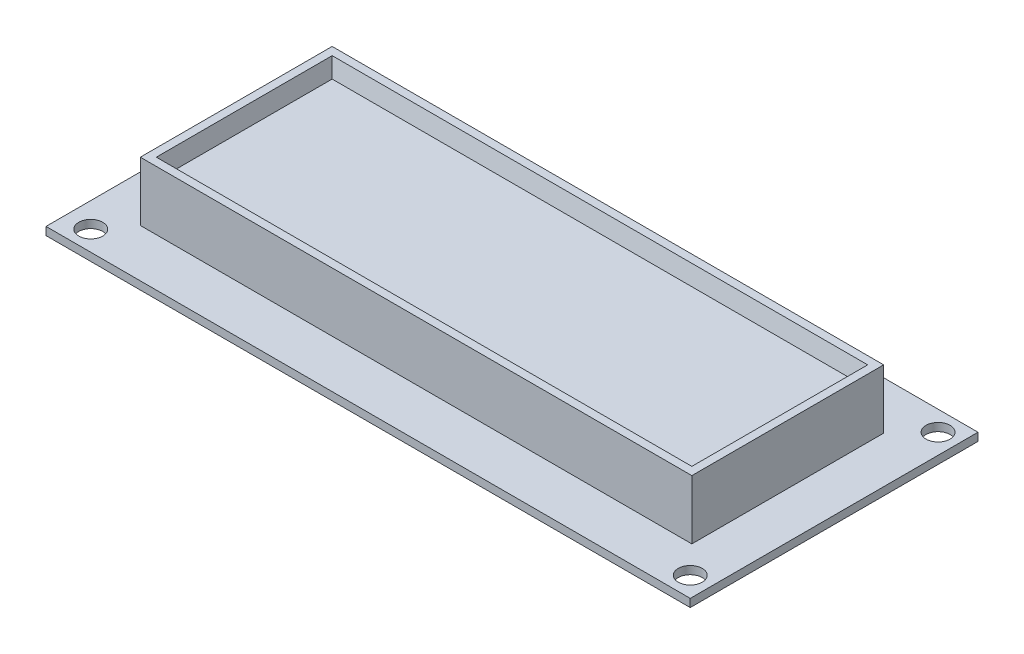
SolidWorks part; units mm, degrees
ref_plane "Front Plane" through (0, 0, 0) normal (0, 0, 1) x (1, 0, 0)
ref_plane "Top Plane" through (0, 0, 0) normal (0, 1, 0) x (1, 0, 0)
ref_plane "Right Plane" through (0, 0, 0) normal (1, 0, 0) x (0, 0, -1)
sketch "Sketch1" plane through (0, 0, 0) normal (0, 1, 0) x (1, 0, 0)
  line L1 (0, 0) -> (80.6, 0)
  line L2 (0, 0) -> (0, 36)
  line L3 (0, 36) -> (80.6, 36)
  line L4 (80.6, 0) -> (80.6, 36)
  dimension "D1" = 36
  dimension "D2" = 80.6
extrude "Boss-Extrude1" add sketch "Sketch1" along normal blind 1
sketch "Sketch2" plane through (0, 1, 0) normal (0, 1, 0) x (1, 0, 0)
  line L0 (80.6, 36) -> (0, 36) construction
  line L1 (5.8, 6) -> (74.8, 6)
  line L2 (5.8, 6) -> (5.8, 30)
  line L3 (5.8, 30) -> (74.8, 30)
  line L4 (74.8, 6) -> (74.8, 30)
  line L5 (0, 36) -> (0, 0) construction
  line L6 (80.6, 0) -> (80.6, 36) construction
  line L7 (0, 0) -> (80.6, 0) construction
  dimension "D1" = 69
  dimension "D2" = 24
  dimension "D3" = 6
  dimension "D4" = 5.8
  dimension "D5" = 5.8
  dimension "D6" = 6
extrude "Boss-Extrude2" add sketch "Sketch2" along normal blind 7.4
sketch "Sketch3" plane through (0, 1, 0) normal (0, 1, 0) x (1, 0, 0)
  line L0 (80.6, 0) -> (80.6, 36) construction
  line L1 (80.6, 36) -> (0, 36) construction
  line L2 (0, 0) -> (80.6, 0) construction
  circle A0 centre (3.1, 33.5) radius 1.5
  circle A1 centre (3.1, 2.5) radius 1.5
  circle A2 centre (78.1, 2.5) radius 1.5
  circle A3 centre (78.1, 33.5) radius 1.5
  dimension "D1" = 3
  dimension "D2" = 3
  dimension "D3" = 3
  dimension "D4" = 3
  dimension "D5" = 75
  dimension "D6" = 75
  dimension "D7" = 31
  dimension "D8" = 31
  dimension "D9" = 2.5
  dimension "D10" = 2.5
  dimension "D11" = 2.5
  dimension "D12" = 2.5
  dimension "D13" = 2.5
  dimension "D14" = 2.5
extrude "Cut-Extrude1" cut sketch "Sketch3" against normal blind 7.4
sketch "Sketch4" plane through (0, 8.4, 0) normal (0, 1, 0) x (1, 0, 0)
  line L0 (74.8, 30) -> (5.8, 30) construction
  line L1 (6.8, 29) -> (73.8, 29)
  line L2 (6.8, 29) -> (6.8, 7)
  line L3 (6.8, 7) -> (73.8, 7)
  line L4 (73.8, 29) -> (73.8, 7)
  line L5 (5.8, 6) -> (74.8, 6) construction
  line L6 (5.8, 30) -> (5.8, 6) construction
  line L7 (74.8, 6) -> (74.8, 30) construction
  dimension "D1" = 1
  dimension "D2" = 1
  dimension "D3" = 1
  dimension "D4" = 1
extrude "Cut-Extrude2" cut sketch "Sketch4" against normal blind 2 draft 15
